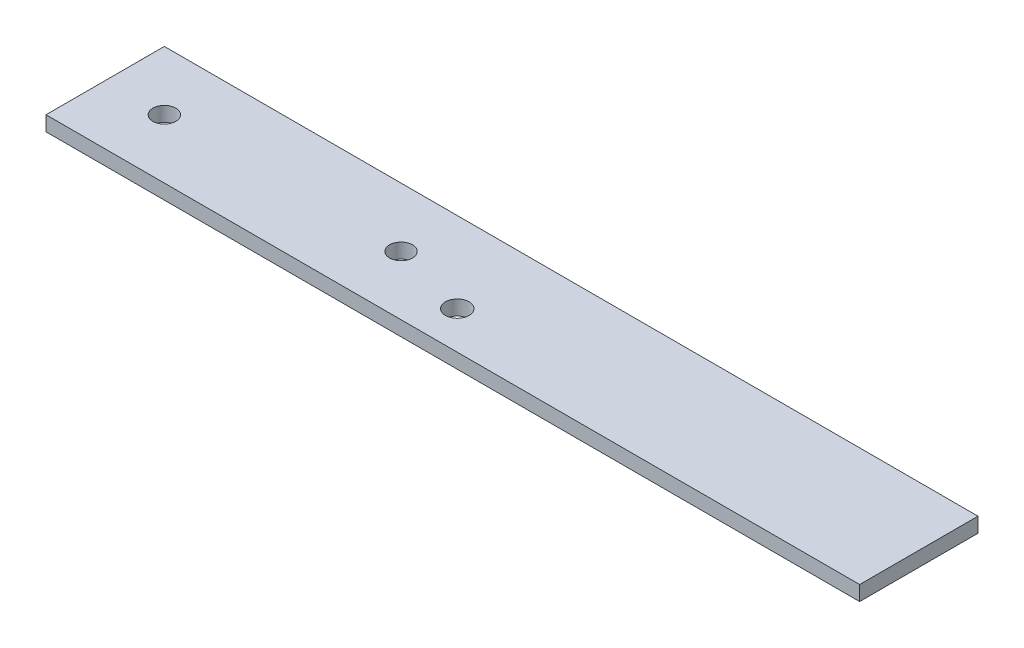
SolidWorks part; units mm, degrees
ref_plane "Plan de face" through (0, 0, 0) normal (0, 0, 1) x (1, 0, 0)
ref_plane "Plan de dessus" through (0, 0, 0) normal (0, 1, 0) x (1, 0, 0)
ref_plane "Plan de droite" through (0, 0, 0) normal (1, 0, 0) x (0, 0, -1)
sketch "Esquisse1" plane through (0, 0, 0) normal (0, 1, 0) x (1, 0, 0)
  line L0 (0, 0) -> (0, 16)
  line L1 (0, 16) -> (110, 16)
  line L2 (110, 16) -> (110, 0)
  line L3 (110, 0) -> (0, 0)
  line L4 (55, 16) -> (55, 0) construction
  circle A0 centre (8, 8) radius 1.55
  circle A1 centre (40, 8) radius 1.55
  circle A2 centre (50.5, 5.1) radius 1.6
  dimension "D3" = 3.1
  dimension "D7" = 3.2
  dimension "D1" = 16
  dimension "D2" = 110
  dimension "D4" = 8
  dimension "D5" = 8
  dimension "D6" = 32
  dimension "D8" = 10.5
  dimension "D9" = 5.1
extrude "Boss.-Extru.1" add sketch "Esquisse1" along normal blind 2
